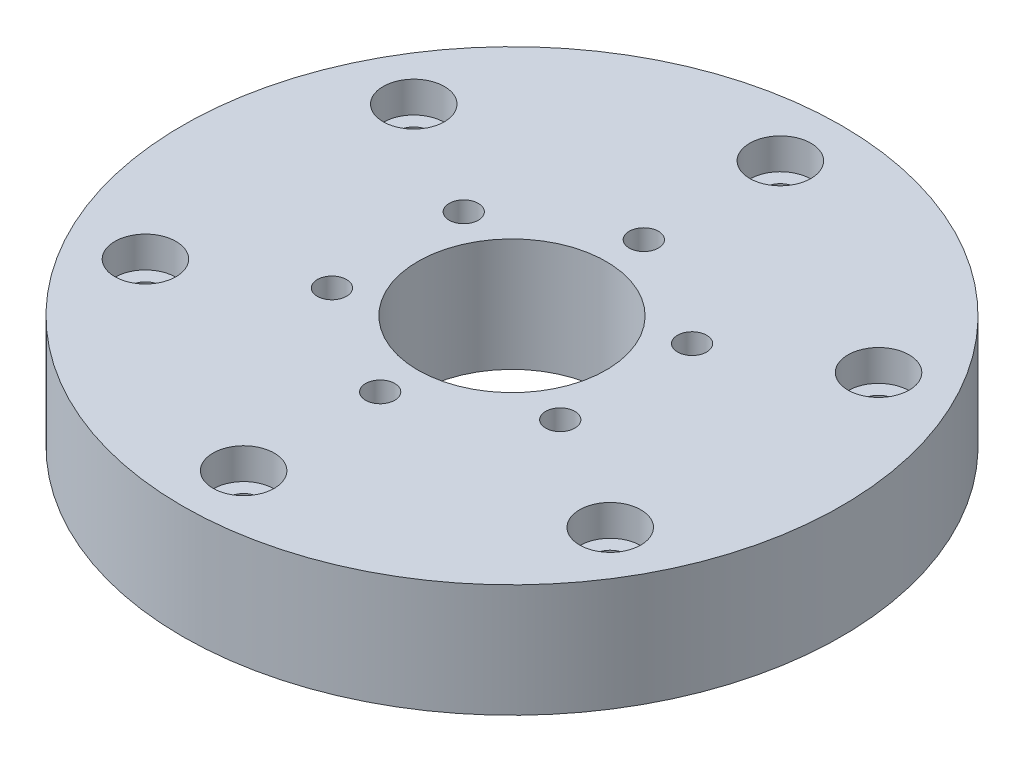
SolidWorks part; units mm, degrees
ref_plane "前视基准面" through (0, 0, 0) normal (0, 0, 1) x (1, 0, 0)
ref_plane "上视基准面" through (0, 0, 0) normal (0, 1, 0) x (1, 0, 0)
ref_plane "右视基准面" through (0, 0, 0) normal (1, 0, 0) x (0, 0, -1)
sketch "草图1" plane through (0, 0, 0) normal (0, 1, 0) x (1, 0, 0)
  circle A0 centre (0, 0) radius 10
  circle A1 centre (0, 0) radius 35
  circle A2 centre (0, 0) radius 14 construction
  circle A3 centre (0, 14) radius 1.55
  circle A4 centre (12.1244, 7) radius 1.55
  circle A5 centre (12.1244, -7) radius 1.55
  circle A6 centre (0, -14) radius 1.55
  circle A7 centre (-12.1244, -7) radius 1.55
  circle A8 centre (-12.1244, 7) radius 1.55
  circle A9 centre (0, 0) radius 28.5 construction
  circle A10 centre (0, 28.5) radius 1.7
  circle A11 centre (24.6817, 14.25) radius 1.7
  circle A12 centre (24.6817, -14.25) radius 1.7
  circle A13 centre (0, -28.5) radius 1.7
  circle A14 centre (-24.6817, -14.25) radius 1.7
  circle A15 centre (-24.6817, 14.25) radius 1.7
  point P20 (0, 0)
  point P34 (0, 0)
  dimension "D1" = 20
  dimension "D2" = 70
  dimension "D3" = 28
  dimension "D4" = 3.1
  dimension "D6" = 57
  dimension "D7" = 3.4
  dimension "D5" = 6
  dimension "D8" = 6
extrude "凸台-拉伸1" add sketch "草图1" along normal blind 12
ref_plane "基准面1" through (0, 12, 0) normal (0, 1, 0) x (1, 0, 0)
sketch "草图2" plane through (0, 12, 0) normal (0, 1, 0) x (1, 0, 0)
  circle A0 centre (0, 0) radius 28.5 construction
  circle A1 centre (0, 28.5) radius 3.25
  circle A2 centre (24.6817, 14.25) radius 3.25
  circle A3 centre (24.6817, -14.25) radius 3.25
  circle A4 centre (0, -28.5) radius 3.25
  circle A5 centre (-24.6817, -14.25) radius 3.25
  circle A6 centre (-24.6817, 14.25) radius 3.25
  point P19 (0, 0)
  dimension "D1" = 6.5
  dimension "D2" = 6
extrude "切除-拉伸1" cut sketch "草图2" against normal blind 3.3
